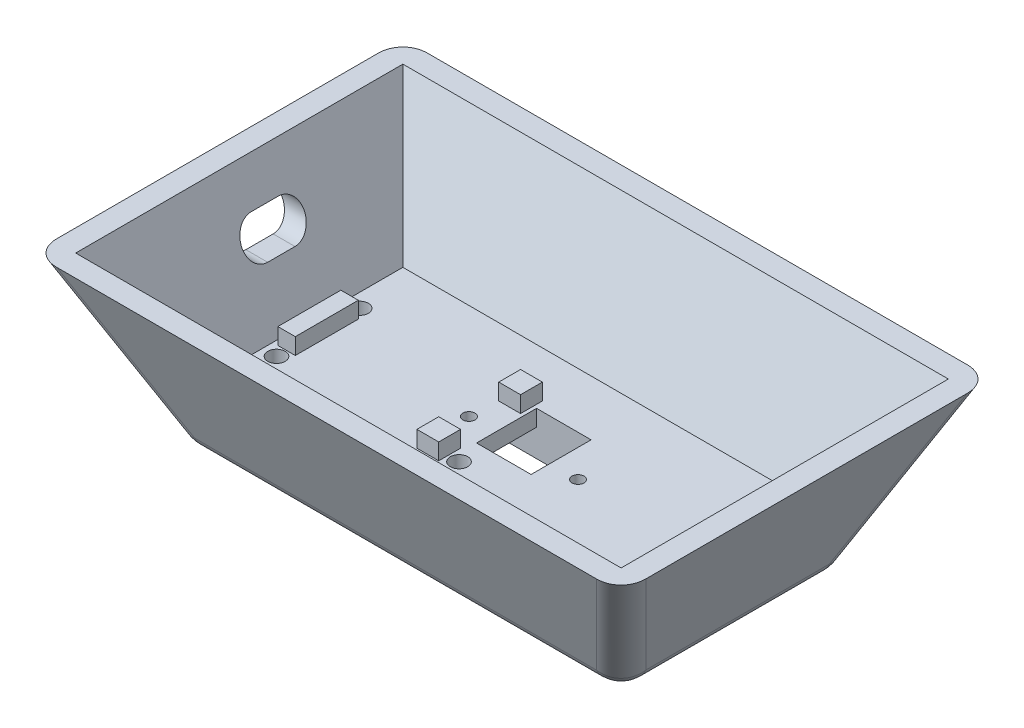
SolidWorks part; units mm, degrees
ref_plane "Front Plane" through (0, 0, 0) normal (0, 0, 1) x (1, 0, 0)
ref_plane "Top Plane" through (0, 0, 0) normal (0, 1, 0) x (1, 0, 0)
ref_plane "Right Plane" through (0, 0, 0) normal (1, 0, 0) x (0, 0, -1)
sketch "Sketch1" plane through (0, 0, 0) normal (0, 1, 0) x (1, 0, 0)
  line L1 (-40, 20) -> (40, 20)
  line L2 (-40, 20) -> (-40, -20)
  line L3 (-40, -20) -> (40, -20)
  line L4 (40, 20) -> (40, -20)
  line L5 (-40, 20) -> (40, -20) construction
  line L6 (-40, -20) -> (40, 20) construction
  point P0 (0, 0)
  dimension "D1" = 40
  dimension "D2" = 80
extrude "Boss-Extrude1" add sketch "Sketch1" along normal blind 30 draft 25 draft outward yes
sketch "Sketch2" plane through (0, 0, 0) normal (0, -1, 0) x (1, 0, 0)
  line L0 (0, 9.6) -> (0, 20) construction
  line L1 (-15.1, 9.6) -> (15.1, 9.6)
  line L2 (-15.1, 9.6) -> (-15.1, -9.6)
  line L3 (-15.1, -9.6) -> (15.1, -9.6)
  line L4 (15.1, 9.6) -> (15.1, -9.6)
  line L5 (-15.1, 9.6) -> (15.1, -9.6) construction
  line L6 (-15.1, -9.6) -> (15.1, 9.6) construction
  line L7 (-40, 20) -> (40, 20) construction
  point P0 (0, 0)
  dimension "D1" = 19.2
  dimension "D2" = 30.2
  dimension "D3" = 10.4
extrude "Cut-Extrude1" cut sketch "Sketch2" against normal blind 5
sketch "Sketch3" plane through (0, 30, 0) normal (0, 1, 0) x (1, 0, 0)
  line L17 (-49.9892, 29.9892) -> (-49.9892, -29.9892)
  line L18 (-49.9892, -29.9892) -> (49.9892, -29.9892)
  line L19 (49.9892, -29.9892) -> (49.9892, 29.9892)
  line L20 (49.9892, 29.9892) -> (-49.9892, 29.9892)
  line L21 (-49.9892, 29.9892) -> (-49.9892, -29.9892)
  line L22 (-49.9892, -29.9892) -> (49.9892, -29.9892)
  line L23 (49.9892, -29.9892) -> (49.9892, 29.9892)
  line L24 (49.9892, 29.9892) -> (-49.9892, 29.9892)
  dimension "D2" = 4
extrude "Cut-Extrude3" cut sketch "Sketch3" against normal blind 22 draft 25
sketch "Sketch5" plane through (0, 5, 0) normal (0, -1, 0) x (1, 0, 0)
  line L0 (0, -2.1) -> (-10, -2.1) construction
  line L1 (0, -2.1) -> (10, -2.1) construction
  line L2 (-5.1, -2.6) -> (-5.1, 1.4) construction
  line L4 (-5.1, 1.4) -> (4.9, 1.4) construction
  line L5 (-15.1, 9.6) -> (-15.1, -9.6) construction
  line L6 (4.9, 1.4) -> (-5.1, 1.4)
  line L7 (4.9, 1.4) -> (4.9, -9.6)
  line L8 (4.9, -9.6) -> (-5.1, -9.6)
  line L9 (-5.1, 1.4) -> (-5.1, -9.6)
  line L11 (-15.1, -9.6) -> (15.1, -9.6) construction
  circle A0 centre (-10, -2.1) radius 1.1
  circle A1 centre (10, -2.1) radius 1.1
  dimension "D3" = 2.2
  dimension "D4" = 2.2
  dimension "D1" = 10
  dimension "D2" = 10
  dimension "D5" = 4
  dimension "D6" = 10
  dimension "D7" = 7.5
  dimension "D8" = 11
  dimension "D9" = 10
extrude "Cut-Extrude4" cut sketch "Sketch5" against normal up to next
sketch "Sketch6" plane through (0, 8, 0) normal (0, 1, 0) x (1, 0, 0)
  line L0 (-5.1, 4.1) -> (-39.7305, 4.1) construction
  line L1 (-5.1, -1.4) -> (-5.1, 9.6) construction
  line L2 (-39.7305, 19.7305) -> (-39.7305, -19.7305) construction
  line L3 (-39.7305, 4.1) -> (-39.7305, -8.7) construction
  line L4 (-39.7305, -8.7) -> (-1.7305, -8.7) construction
  line L5 (-39.7305, 4.1) -> (-39.7305, 12.3) construction
  line L6 (-39.7305, -8.7) -> (-39.7305, -5.98) construction
  line L7 (-39.7305, 12.3) -> (-1.7305, 12.3)
  line L8 (-39.7305, 12.3) -> (-39.7305, -8.7)
  line L9 (-39.7305, -8.7) -> (-1.7305, -8.7)
  line L10 (-1.7305, 12.3) -> (-1.7305, -8.7)
  line L11 (-39.7305, -5.98) -> (-37.1905, -5.98) construction
  line L12 (-39.7305, -8.7) -> (-39.7305, 9.27) construction
  line L13 (-39.7305, 9.27) -> (-37.1905, 9.27) construction
  line L14 (-39.7305, -5.98) -> (-3.7305, -5.98) construction
  circle A0 centre (-37.1905, -5.98) radius 1.6
  circle A1 centre (-37.1905, 9.27) radius 1.6
  circle A2 centre (-3.7305, -5.98) radius 1.6
  dimension "D2" = 3.2
extrude "PCB_HeatSetInserts" cut sketch "Sketch6" against normal blind 4.75 contours A1 | A0 | A2
sketch "Sketch7" plane through (0, 8, 0) normal (0, 1, 0) x (1, 0, 0)
  line L0 (-9.7305, -3.7) -> (-5.7305, -3.7)
  line L1 (-38.7905, 9.27) -> (-38.7905, -5.98) construction
  line L2 (-35.5905, 9.27) -> (-35.5905, -5.98) construction
  line L3 (-37.1905, 7.67) -> (-37.1905, 6.92) construction
  line L4 (-37.1905, -4.38) -> (-37.1905, -4.13) construction
  line L5 (-9.7305, -3.7) -> (-9.7305, -7.7)
  line L6 (-38.7905, 7.42) -> (-35.5905, 7.42)
  line L7 (-38.7905, 7.42) -> (-38.7905, -4.13)
  line L8 (-38.7905, -4.13) -> (-35.5905, -4.13)
  line L9 (-35.5905, 7.42) -> (-35.5905, -4.13)
  line L10 (-9.7305, 11.3) -> (-5.7305, 11.3)
  line L11 (-9.7305, 11.3) -> (-9.7305, 7.3)
  line L12 (-9.7305, 7.3) -> (-5.7305, 7.3)
  line L13 (-5.7305, 11.3) -> (-5.7305, 7.3)
  line L14 (-9.7305, -7.7) -> (-5.7305, -7.7)
  line L15 (-5.7305, -3.7) -> (-5.7305, -7.7)
  line L16 (-37.1905, -5.98) -> (-39.7305, -5.98) construction
  line L17 (-37.1905, -5.98) -> (-37.1905, -8.7) construction
  line L18 (-39.7305, 19.7305) -> (-39.7305, -19.7305) construction
  line L19 (-39.7305, -8.7) -> (-9.7305, -8.7) construction
  line L20 (-9.7305, -8.7) -> (-9.7305, -7.7) construction
  line L21 (-9.7305, -3.7) -> (-9.7305, 7.3) construction
  circle A0 centre (-37.1905, 9.27) radius 1.6 construction
  circle A1 centre (-37.1905, 9.27) radius 1.6 construction
  circle A2 centre (-37.1905, -5.98) radius 1.6 construction
  circle A3 centre (-37.1905, -5.98) radius 1.6 construction
  point P31 (-39.7305, -8.7)
  dimension "D1" = 0.75
  dimension "D2" = 2.54
  dimension "D3" = 2.72
  dimension "D4" = 30
  dimension "D5" = 4
  dimension "D6" = 4
  dimension "D7" = 4
  dimension "D8" = 4
  dimension "D9" = 11
  dimension "D10" = 1
extrude "Boss-Extrude3" add sketch "Sketch7" along normal blind 3
fillet "Fillet1" radius 5 8 edges at (-40, 0, 0) (0, 0, 20) (40, 0, 0) (0, 0, -20) (-46.9946, 15, 26.9946) (46.9946, 15, 26.9946) (46.9946, 15, -26.9946) (-46.9946, 15, -26.9946)
sketch "Sketch10" plane through (-35.5905, 0, 0) normal (1, 0, 0) x (0, 0, -1)
  line L0 (1.645, 11) -> (1.645, 20.25) construction
  line L1 (-4.13, 11) -> (7.42, 11) construction
  line L2 (-0.855, 20.25) -> (4.145, 20.25) construction
  line L3 (-0.855, 23.5) -> (4.145, 23.5)
  line L4 (-0.855, 17) -> (4.145, 17)
  arc A0 (-0.855, 23.5) -> (-0.855, 17) centre (-0.855, 20.25) ccw
  arc A1 (4.145, 17) -> (4.145, 23.5) centre (4.145, 20.25) ccw
  point P6 (1.645, 20.25)
extrude "USB-C Cutout" cut sketch "Sketch10" against normal up to next contours L4 A1 L3 A0
